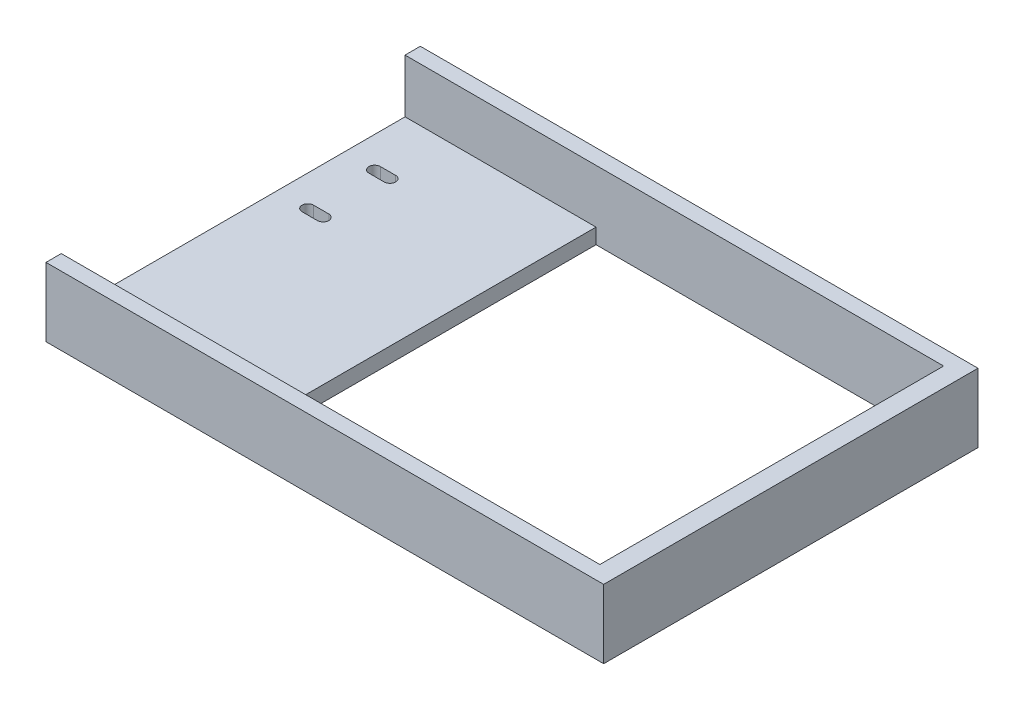
SolidWorks part; units mm, degrees
ref_plane "前视基准面" through (0, 0, 0) normal (0, 0, 1) x (1, 0, 0)
ref_plane "上视基准面" through (0, 0, 0) normal (0, 1, 0) x (1, 0, 0)
ref_plane "右视基准面" through (0, 0, 0) normal (1, 0, 0) x (0, 0, -1)
sketch "草图1" plane through (0, 0, 0) normal (0, 1, 0) x (1, 0, 0)
  line L1 (-85.9688, 46.375) -> (60.0312, 46.375)
  line L2 (-85.9688, 46.375) -> (-85.9688, -51.625)
  line L3 (-85.9688, -51.625) -> (60.0313, -51.625)
  line L4 (60.0312, 46.375) -> (60.0313, -51.625)
  line L5 (-85.9688, 46.375) -> (60.0313, -51.625) construction
  line L6 (-85.9688, -51.625) -> (60.0312, 46.375) construction
  point P4 (-12.9688, -2.625)
  dimension "D1" = 98
  dimension "D2" = 146
extrude "凸台-拉伸1" add sketch "草图1" along normal blind 18
sketch "草图2" plane through (0, 18, 0) normal (0, 1, 0) x (1, 0, 0)
  line L0 (-85.9688, 46.375) -> (-85.9688, -51.625) construction
  line L1 (-85.9688, 42.375) -> (55.0313, 42.375)
  line L2 (-85.9688, 42.375) -> (-85.9688, -47.625)
  line L3 (-85.9688, -47.625) -> (55.0313, -47.625)
  line L4 (55.0313, 42.375) -> (55.0313, -47.625)
  line L5 (-85.9688, 42.375) -> (55.0313, -47.625) construction
  line L6 (-85.9688, -47.625) -> (55.0313, 42.375) construction
  line L7 (60.0313, -51.625) -> (60.0312, 46.375) construction
  line L8 (60.0312, 46.375) -> (-85.9688, 46.375) construction
  line L9 (-85.9688, -51.625) -> (60.0313, -51.625) construction
  point P4 (-15.4688, -2.625)
  dimension "D1" = 5
  dimension "D2" = 4
  dimension "D3" = 4
extrude "切除-拉伸1" cut sketch "草图2" against normal blind 14
sketch "草图3" plane through (0, 4, 0) normal (0, 1, 0) x (1, 0, 0)
  line L0 (55.0313, 42.375) -> (-85.9688, 42.375) construction
  line L1 (-35.9688, 42.375) -> (55.0313, 42.375)
  line L2 (-35.9688, 42.375) -> (-35.9687, -47.625)
  line L3 (-35.9687, -47.625) -> (55.0313, -47.625)
  line L4 (55.0313, 42.375) -> (55.0313, -47.625)
  line L5 (-35.9688, 42.375) -> (55.0313, -47.625) construction
  line L6 (-35.9687, -47.625) -> (55.0313, 42.375) construction
  line L7 (-85.9688, 42.375) -> (-85.9688, -47.625) construction
  point P4 (9.5313, -2.625)
  dimension "D1" = 50
extrude "切除-拉伸2" cut sketch "草图3" against normal blind 17
sketch "草图5" plane through (0, 4, 0) normal (0, 1, 0) x (1, 0, 0)
  line L0 (-75.9688, 42.375) -> (-75.9688, -47.625) construction
  line L1 (-35.9688, 42.375) -> (-85.9688, 42.375) construction
  line L2 (-85.9688, -47.625) -> (-35.9687, -47.625) construction
  line L3 (-85.9688, 42.375) -> (-85.9688, -47.625) construction
  line L4 (-73.9314, 26.375) -> (-77.9314, 26.375) construction
  line L5 (-73.9314, 24.875) -> (-77.9314, 24.875)
  line L6 (-73.9314, 27.875) -> (-77.9314, 27.875)
  line L7 (-73.9314, 8.875) -> (-77.9314, 8.875) construction
  line L8 (-73.9314, 7.375) -> (-77.9314, 7.375)
  line L9 (-73.9314, 10.375) -> (-77.9314, 10.375)
  arc A0 (-73.9314, 24.875) -> (-73.9314, 27.875) centre (-73.9314, 26.375) ccw
  arc A1 (-77.9314, 27.875) -> (-77.9314, 24.875) centre (-77.9314, 26.375) ccw
  arc A2 (-73.9314, 7.375) -> (-73.9314, 10.375) centre (-73.9314, 8.875) ccw
  arc A3 (-77.9314, 10.375) -> (-77.9314, 7.375) centre (-77.9314, 8.875) ccw
  point P10 (-75.9314, 26.375)
  point P15 (-75.9314, 8.875)
  dimension "D1" = 10
  dimension "D2" = 16
  dimension "D3" = 17.5
extrude "切除-拉伸3" cut sketch "草图5" against normal blind 17
